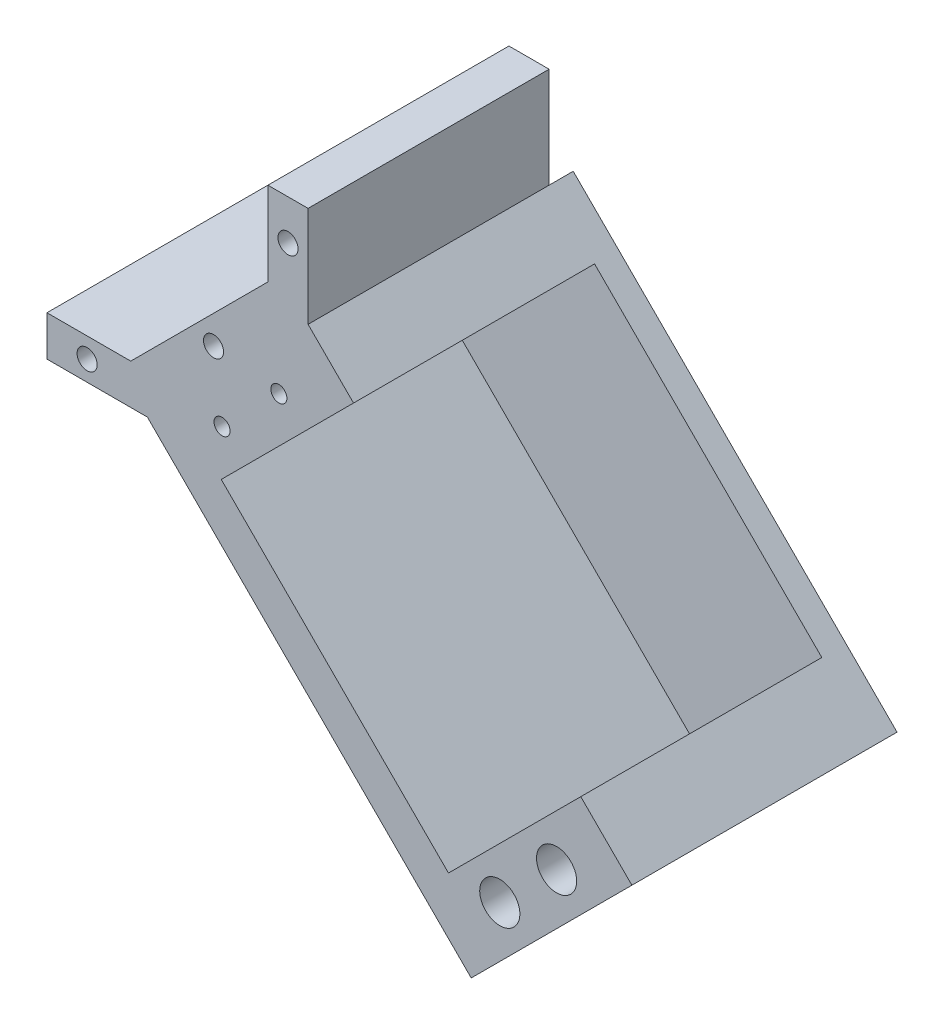
SolidWorks part; units mm, degrees
ref_plane "Front Plane" through (0, 0, 0) normal (0, 0, 1) x (1, 0, 0)
ref_plane "Top Plane" through (0, 0, 0) normal (0, 1, 0) x (1, 0, 0)
ref_plane "Right Plane" through (0, 0, 0) normal (1, 0, 0) x (0, 0, -1)
sketch "Model" plane through (0, 0, 0) normal (0, 0, 1) x (1, 0, 0)
  line L0 (25.1007, 10.3343) -> (45.1007, 30.3343)
  line L1 (25.1007, 10.3343) -> (12.6007, 10.3343)
  line L2 (25.1007, 10.3343) -> (45.1007, 30.3343)
  line L3 (30.7575, 4.6775) -> (50.7575, 24.6775)
  line L4 (23.0296, 15.3343) -> (40.1007, 32.4054)
  line L5 (40.1007, 42.8343) -> (45.1007, 42.8343)
  line L6 (25.1007, 10.3343) -> (12.6007, 10.3343)
  line L7 (23.0296, 15.3343) -> (12.6007, 15.3343)
  line L8 (12.6007, 10.3343) -> (12.6007, 15.3343)
  line L9 (45.1007, 42.8343) -> (45.1007, 30.3343)
  line L10 (40.1007, 42.8343) -> (40.1007, 32.4054)
  line L11 (45.1007, 30.3343) -> (50.7575, 24.6775)
  line L12 (25.1007, 10.3343) -> (30.7575, 4.6775)
  circle A0 centre (17.6007, 12.8343) radius 1.25
  circle A1 centre (42.6007, 37.8343) radius 1.25
  circle A2 centre (33.3329, 22.1021) radius 1.25
  circle A3 centre (34.3936, 13.9704) radius 1
  circle A4 centre (41.4647, 21.0414) radius 1
extrude "Boss-Extrude1" add sketch "Model" along normal blind 30 contours L0 L12 L3 L11 A4 A3 | L5 L10 L4 L7 L8 L1 L0 L9 A2 A1 A0
sketch "Sketch3" plane through (0, 0, 0) normal (0, 0, -1) x (-1, 0, 0)
  line L1 (-30.7575, 4.6775) -> (-59.0418, -23.6068)
  line L2 (-59.0418, -23.6068) -> (-79.0418, -3.6068)
  line L3 (-62.5774, -20.0713) -> (-79.0418, -3.6068)
  line L4 (-65.4058, -29.9708) -> (-85.4058, -9.9708)
  line L5 (-85.4058, -9.9708) -> (-79.0418, -3.6068)
  line L6 (-65.4058, -29.9708) -> (-59.0418, -23.6068)
  line L7 (-34.2931, 8.213) -> (-62.5774, -20.0713)
  line L8 (-72.8765, -9.7721) -> (-79.1897, -16.1869) construction
  line L9 (-59.0418, -23.6068) -> (-79.0418, -3.6068) construction
  line L10 (-65.7546, -16.894) -> (-72.1694, -23.2072) construction
  line L11 (-76.0331, -12.9795) -> (-68.962, -20.0506) construction
  line L12 (-34.2931, 8.213) -> (-30.7575, 4.6775)
  circle A0 centre (-76.0331, -12.9795) radius 2.5
  circle A1 centre (-68.962, -20.0506) radius 2.5
  dimension "D4" = 5
  dimension "D5" = 5
  dimension "D1" = 40
  dimension "D2" = 9
  dimension "D3" = 5
extrude "Boss-Extrude2" add sketch "Sketch3" against normal blind 30
sketch "Sketch7" plane through (0, 0, 0) normal (0, 0, -1) x (-1, 0, 0)
  line L0 (-45.1007, 30.3343) -> (-25.1007, 10.3343)
  line L14 (-45.1007, 30.3343) -> (-50.7575, 24.6775)
  line L15 (-50.7575, 24.6775) -> (-34.2931, 8.213)
  line L16 (-34.2931, 8.213) -> (-62.5774, -20.0713)
  line L17 (-62.5774, -20.0713) -> (-79.0418, -3.6068)
  line L18 (-79.0418, -3.6068) -> (-85.4058, -9.9708)
  line L19 (-85.4058, -9.9708) -> (-65.4058, -29.9708)
  line L20 (-65.4058, -29.9708) -> (-25.1007, 10.3343)
  line L21 (-25.1007, 10.3343) -> (-12.6007, 10.3343)
  line L22 (-12.6007, 10.3343) -> (-12.6007, 15.3343)
  line L23 (-12.6007, 15.3343) -> (-23.0296, 15.3343)
  line L24 (-23.0296, 15.3343) -> (-40.1007, 32.4054)
  line L25 (-40.1007, 32.4054) -> (-40.1007, 42.8343)
  line L26 (-40.1007, 42.8343) -> (-45.1007, 42.8343)
  line L27 (-45.1007, 42.8343) -> (-45.1007, 30.3343)
  line L28 (-45.1007, 30.3343) -> (-50.7575, 24.6775)
  line L29 (-50.7575, 24.6775) -> (-34.2931, 8.213)
  line L30 (-34.2931, 8.213) -> (-62.5774, -20.0713)
  line L31 (-62.5774, -20.0713) -> (-79.0418, -3.6068)
  line L32 (-79.0418, -3.6068) -> (-85.4058, -9.9708)
  line L33 (-85.4058, -9.9708) -> (-65.4058, -29.9708)
  line L34 (-65.4058, -29.9708) -> (-25.1007, 10.3343)
  circle A0 centre (-68.962, -20.0506) radius 2.5 construction
  circle A1 centre (-76.0331, -12.9795) radius 2.5 construction
  circle A2 centre (-34.3936, 13.9704) radius 1 construction
  circle A3 centre (-41.4647, 21.0414) radius 1 construction
  circle A4 centre (-68.962, -20.0506) radius 2.5
  circle A5 centre (-76.0331, -12.9795) radius 2.5
  circle A6 centre (-34.3936, 13.9704) radius 1
  circle A7 centre (-41.4647, 21.0414) radius 1
  dimension "D1" = 0
extrude "Boss-Extrude5" add sketch "Sketch7" along normal blind 3
sketch "Sketch8" plane through (0, 0, -3) normal (0, 0, -1) x (-1, 0, 0)
  line L0 (-50.7575, 24.6775) -> (-34.2931, 8.213) construction
  line L1 (-50.7575, 24.6775) -> (-34.2931, 8.213)
  line L2 (-62.5774, -20.0713) -> (-79.0418, -3.6068) construction
  line L3 (-62.5774, -20.0713) -> (-79.0418, -3.6068)
  line L4 (-34.2931, 8.213) -> (-62.5774, -20.0713) construction
  line L5 (-34.2931, 8.213) -> (-62.5774, -20.0713)
  line L6 (-79.0418, -3.6068) -> (-50.7575, 24.6775)
extrude "Boss-Extrude6" add sketch "Sketch8" against normal blind 3
